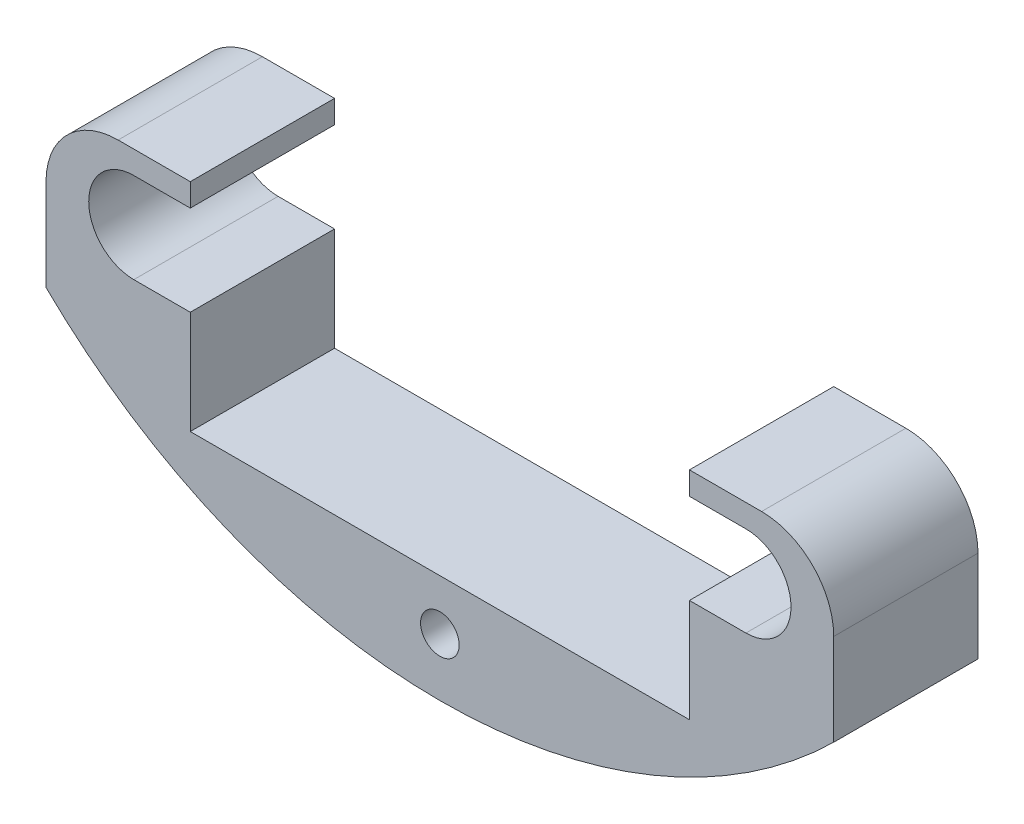
SolidWorks part; units mm, degrees
ref_plane "Front Plane" through (0, 0, 0) normal (0, 0, 1) x (1, 0, 0)
ref_plane "Top Plane" through (0, 0, 0) normal (0, 1, 0) x (1, 0, 0)
ref_plane "Right Plane" through (0, 0, 0) normal (1, 0, 0) x (0, 0, -1)
sketch "Sketch1" plane through (0, 0, 0) normal (0, 0, 1) x (1, 0, 0)
  circle A0 centre (0, 0) radius 49.53
  dimension "D1" = 99.06
sketch "Sketch2" plane through (0, 0, 0) normal (0, 0, 1) x (1, 0, 0)
  line L0 (-34.671, -20.955) -> (-34.671, -35.3715)
  line L1 (-34.671, -20.955) -> (-21.971, -20.955)
  line L2 (-21.971, -20.955) -> (-21.971, -22.972)
  line L3 (-21.971, -40.005) -> (0, -40.005)
  line L4 (0, -40.005) -> (0, -49.53)
  line L5 (0, 0) -> (-49.53, 0) construction
  line L6 (0, 0) -> (-26.9408, -26.9408) construction
  line L7 (-26.9408, -22.972) -> (-21.971, -22.972)
  line L8 (-26.9408, -30.9095) -> (-21.971, -30.9095)
  line L9 (-21.971, -30.9095) -> (-21.971, -40.005)
  circle A0 centre (0, 0) radius 49.53 construction
  arc A3 (0, -49.53) -> (-34.671, -35.3715) centre (0, 0) cw
  arc A4 (-26.9408, -22.972) -> (-26.9408, -30.9095) centre (-26.9408, -26.9408) ccw
  dimension "D6" = 45
  dimension "D7" = 7.9375
  dimension "D1" = 21.971
  dimension "D2" = 19.05
  dimension "D3" = 9.525
  dimension "D4" = 12.7
  dimension "D5" = 38.1
extrude "Boss-Extrude1" add sketch "Sketch2" along normal blind 12.7
mirror "Mirror1" about plane through (0, -40.005, 12.7) normal (-1, 0, 0) of "Boss-Extrude1"
fillet "Fillet1" radius 6.35 2 edges at (34.671, -20.955, 6.35) (-34.671, -20.955, 6.35)
hole_wizard "M3 Clearance Hole1" positions "Sketch3" profile "Sketch4" hole size "M3" standard "ANSI Metric" end condition through all
sketch "Sketch3" plane through (0, 0, 12.7) normal (0, 0, 1) x (1, 0, 0)
  point P0 (0, -44.45)
  point P7 (0, 0)
  point P8 (-0.614, -42.545)
  dimension "D1" = 44.45
sketch "Sketch4" plane through (0, -44.45, 12.7) normal (1, 0, 0) x (0, -1, 0)
  line L0 (0, 0) -> (0, 12.7)
  line L1 (0, 12.7) -> (1.7, 12.7)
  line L2 (1.7, 12.7) -> (1.7, 0)
  line L5 (1.7, 0) -> (0, 0)
  line L11 (0, -6.35) -> (0, 107.95) construction
  dimension "Thru Hole Dia." = 3.4
  dimension "Thru Hole Depth" = 12.7
